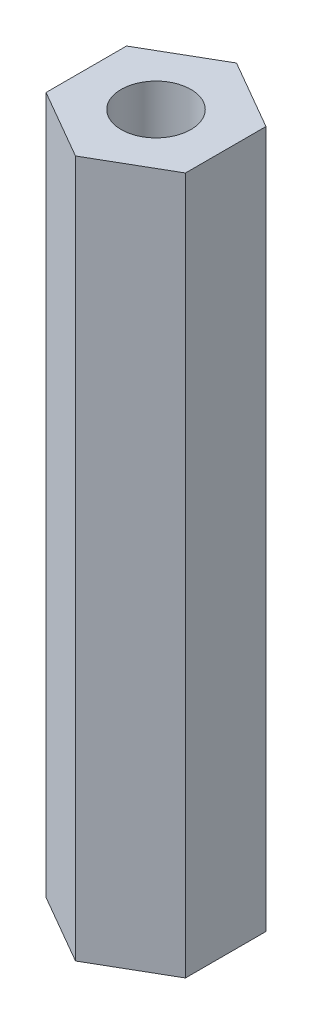
SolidWorks part; units mm, degrees
ref_plane "Front Plane" through (0, 0, 0) normal (0, 0, 1) x (1, 0, 0)
ref_plane "Top Plane" through (0, 0, 0) normal (0, 1, 0) x (1, 0, 0)
ref_plane "Right Plane" through (0, 0, 0) normal (1, 0, 0) x (0, 0, -1)
sketch "Sketch1" plane through (0, 0, 0) normal (0, 1, 0) x (1, 0, 0)
  line L1 (2, -1.1547) -> (2, 1.1547)
  line L2 (2, 1.1547) -> (0, 2.3094)
  line L3 (0, 2.3094) -> (-2, 1.1547)
  line L4 (-2, 1.1547) -> (-2, -1.1547)
  line L5 (-2, -1.1547) -> (0, -2.3094)
  line L6 (0, -2.3094) -> (2, -1.1547)
  circle A0 centre (0, 0) radius 2 construction
  circle A1 centre (0, 0) radius 1
  dimension "D1" = 2
  dimension "D2" = 4
extrude "Boss-Extrude1" add sketch "Sketch1" along normal blind 20
